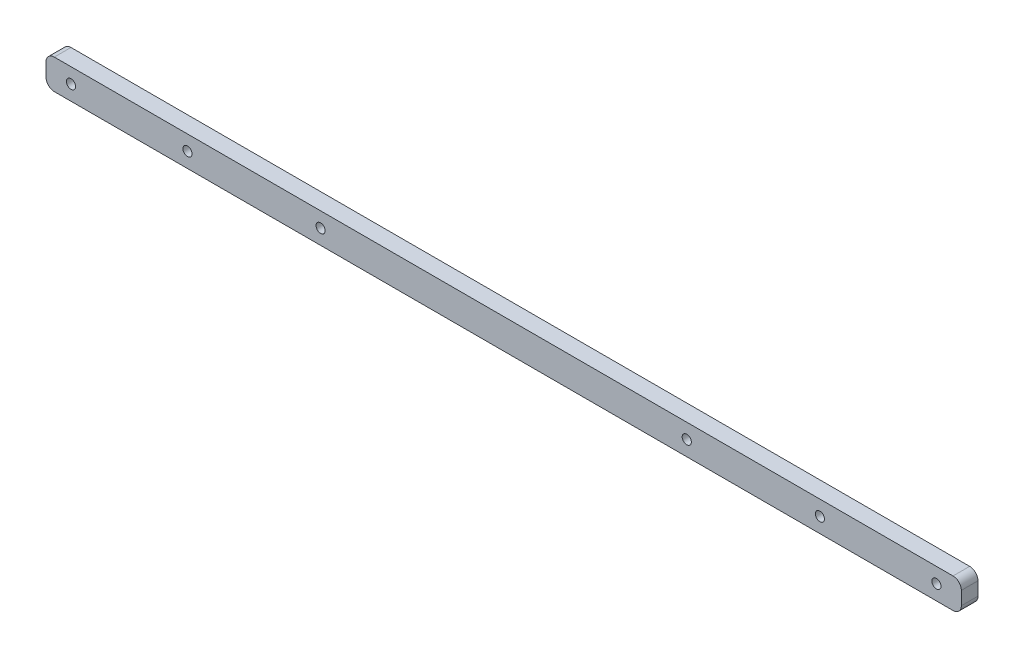
SolidWorks part; units mm, degrees
material "ABS"
ref_plane "Front" through (0, 0, 0) normal (0, 0, 1) x (1, 0, 0)
ref_plane "Top" through (0, 0, 0) normal (0, 1, 0) x (1, 0, 0)
ref_plane "Right" through (0, 0, 0) normal (1, 0, 0) x (0, 0, -1)
sketch "草图1" plane through (0, 0, 0) normal (0, 0, 1) x (1, 0, 0)
  line L0 (0, -9) -> (15, -9) construction
  line L1 (0, 0) -> (550, 0)
  line L2 (0, 0) -> (0, -18)
  line L3 (0, -18) -> (550, -18)
  line L4 (550, 0) -> (550, -18)
  line L5 (15, -9) -> (85, -9) construction
  line L6 (275, 0) -> (275, -18) construction
  circle A0 centre (15, -9) radius 2.75
  circle A1 centre (85, -9) radius 2.75
  circle A2 centre (465, -9) radius 2.75
  circle A3 centre (535, -9) radius 2.75
  dimension "D3" = 5.5
  dimension "D4" = 5.5
  dimension "D1" = 550
  dimension "D2" = 18
  dimension "D5" = 15
  dimension "D6" = 70
extrude "凸台-拉伸1" add sketch "草图1" along normal blind 10
fillet "圆角1" radius 5 4 edges at (550, 0, 5) (550, -18, 5) (0, 0, 5) (0, -18, 5)
sketch "草图2" plane through (0, 0, 10) normal (0, 0, 1) x (1, 0, 0)
  line L0 (275, 0) -> (275, -9) construction
  line L1 (545, 0) -> (5, 0) construction
  line L2 (275, -9) -> (385, -9) construction
  circle A0 centre (385, -9) radius 2.75
  circle A1 centre (165, -9) radius 2.75
  dimension "D1" = 5.5
  dimension "D2" = 9
  dimension "D3" = 110
extrude "切除-拉伸1" cut sketch "草图2" against normal blind 10
